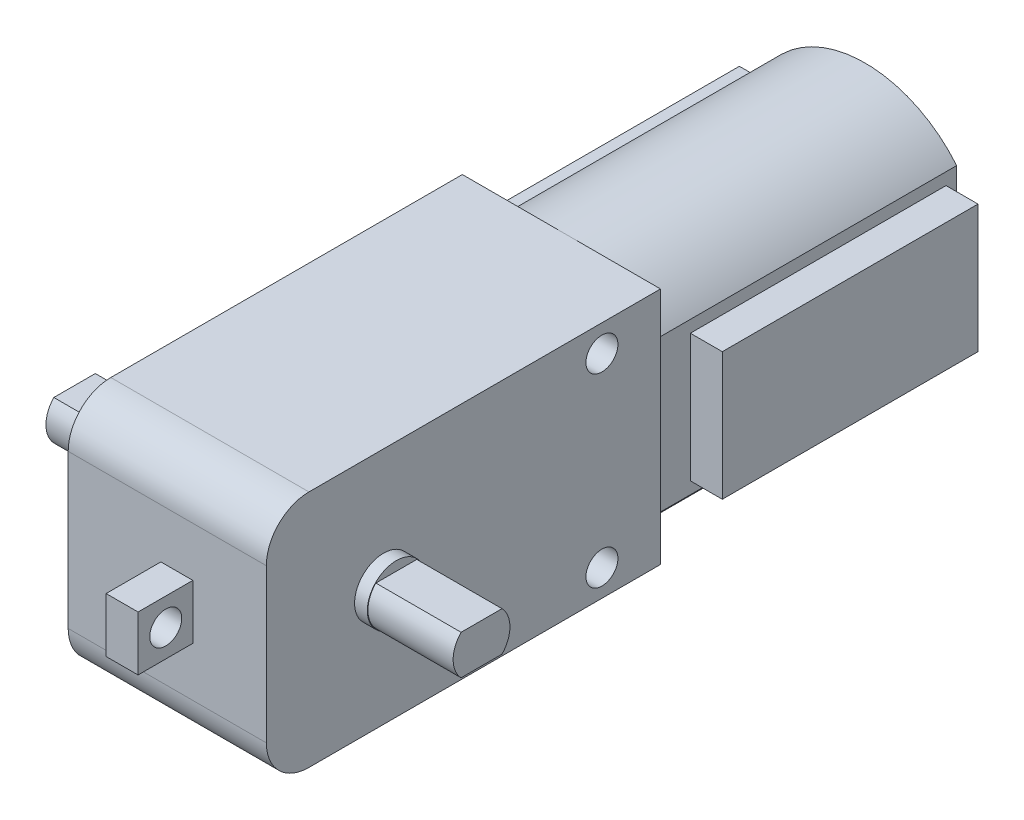
SolidWorks part; units mm, degrees
ref_plane "Front Plane" through (0, 0, 0) normal (0, 0, 1) x (1, 0, 0)
ref_plane "Top Plane" through (0, 0, 0) normal (0, 1, 0) x (1, 0, 0)
ref_plane "Right Plane" through (0, 0, 0) normal (1, 0, 0) x (0, 0, -1)
sketch "Sketch1" plane through (0, 0, 0) normal (1, 0, 0) x (0, 0, -1)
  line L1 (-18.5, 11.2) -> (18.5, 11.2)
  line L2 (-18.5, 11.2) -> (-18.5, -11.2)
  line L3 (-18.5, -11.2) -> (18.5, -11.2)
  line L4 (18.5, 11.2) -> (18.5, -11.2)
  dimension "D1" = 37
  dimension "D2" = 22.4
  dimension "D3" = 18.5
  dimension "D4" = 11.2
extrude "Boss-Extrude1" add sketch "Sketch1" along normal blind 18.6
fillet "Fillet1" radius 4 2 edges at (9.3, -11.2, 18.5) (9.3, 11.2, 18.5)
sketch "Sketch2" plane through (0, 0, 0) normal (-1, 0, 0) x (0, 0, 1)
  line L0 (18.5, 7.2) -> (18.5, -7.2) construction
  circle A0 centre (7.5, 0) radius 3.65
  point P3 (18.5, 0)
  dimension "D1" = 7.3
  dimension "D2" = 11
extrude "Boss-Extrude2" add sketch "Sketch2" along normal blind 1.2
sketch "Sketch3" plane through (-1.2, 0, 0) normal (-1, 0, 0) x (0, 0, 1)
  circle A0 centre (7.5, 0) radius 2.73
  dimension "D1" = 5.46
extrude "Boss-Extrude3" add sketch "Sketch3" along normal blind 1.2
sketch "Sketch4" plane through (-2.4, 0, 0) normal (-1, 0, 0) x (0, 0, 1)
  line L0 (5.5528, -1.85) -> (9.4472, -1.85)
  line L1 (5.5528, 1.85) -> (9.4472, 1.85)
  arc A0 (5.5528, 1.85) -> (5.5528, -1.85) centre (7.5, 0) ccw
  arc A1 (9.4472, -1.85) -> (9.4472, 1.85) centre (7.5, 0) ccw
  dimension "D1" = 3.7
  dimension "D2" = 1.85
extrude "Boss-Extrude4" add sketch "Sketch4" along normal blind 8
sketch "Sketch5" plane through (18.6, 0, 0) normal (1, 0, 0) x (0, 0, -1)
  line L0 (-18.5, 7.2) -> (-18.5, -7.2) construction
  circle A0 centre (-7.5, 0) radius 2.72
  point P2 (-18.5, 0)
  dimension "D1" = 5.44
  dimension "D2" = 11
extrude "Boss-Extrude5" add sketch "Sketch5" along normal blind 1.2
sketch "Sketch6" plane through (19.8, 0, 0) normal (1, 0, 0) x (0, 0, -1)
  line L0 (-9.4199, -1.85) -> (-5.5801, -1.85)
  line L1 (-9.4199, 1.85) -> (-5.5801, 1.85)
  arc A0 (-9.4199, 1.85) -> (-9.4199, -1.85) centre (-7.5, 0) ccw
  arc A1 (-5.5801, -1.85) -> (-5.5801, 1.85) centre (-7.5, 0) ccw
  dimension "D1" = 3.7
  dimension "D2" = 1.85
extrude "Boss-Extrude6" add sketch "Sketch6" along normal blind 8
sketch "Sketch7" plane through (0, 0, 0) normal (-1, 0, 0) x (0, 0, 1)
  line L0 (18.5, 7.2) -> (18.5, -7.2) construction
  circle A0 centre (-3.9, 0) radius 2
  dimension "D1" = 4
  dimension "D2" = 22.4
extrude "Boss-Extrude7" add sketch "Sketch7" along normal blind 2.4
ref_plane "Plane1" through (10.2, 0, 0) normal (-1, 0, 0) x (0, 0, 1)
sketch "Sketch8" plane through (10.2, 0, 0) normal (-1, 0, 0) x (0, 0, 1)
  line L0 (18.5, 7.2) -> (18.5, -7.2) construction
  line L1 (18.5, -2.56) -> (23.64, -2.56)
  line L2 (18.5, -2.56) -> (18.5, 2.56)
  line L3 (18.5, 2.56) -> (23.64, 2.56)
  line L4 (23.64, -2.56) -> (23.64, 2.56)
  dimension "D1" = 5.14
  dimension "D2" = 5.12
  dimension "D3" = 2.56
extrude "Boss-Extrude8" add sketch "Sketch8" along normal mid plane 3
sketch "Sketch11" plane through (0, 0, -18.5) normal (0, 0, -1) x (-1, 0, 0)
  line L0 (-18.6, -11.2) -> (-18.6, 11.2) construction
  line L1 (-18.4, 7.128) -> (-18.4, -7.128)
  line L2 (-1.2, 7.128) -> (-1.2, -7.128)
  arc A0 (-1.2, 7.128) -> (-18.4, 7.128) centre (-9.8, 0) ccw
  arc A1 (-18.4, -7.128) -> (-1.2, -7.128) centre (-9.8, 0) ccw
  dimension "D2" = 22.34
  dimension "D1" = 8.8
  dimension "D3" = 17.2
  dimension "D4" = 8.6
extrude "Boss-Extrude10" add sketch "Sketch11" along normal blind 28
sketch "Sketch12" plane through (18.4, 0, 0) normal (1, 0, 0) x (0, 0, -1)
  line L0 (18.5, -11.2) -> (18.5, 11.2) construction
  line L1 (21.5, 6) -> (45.5, 6)
  line L2 (21.5, 6) -> (21.5, -6)
  line L3 (21.5, -6) -> (45.5, -6)
  line L4 (45.5, 6) -> (45.5, -6)
  dimension "D1" = 3
  dimension "D2" = 6
  dimension "D3" = 24
  dimension "D4" = 12
extrude "Boss-Extrude11" add sketch "Sketch12" along normal blind 3
mirror "Mirror1" about plane through (10.2, 0, 0) normal (-1, 0, 0) of "Boss-Extrude11"
sketch "Sketch13" plane through (18.6, 0, 0) normal (1, 0, 0) x (0, 0, -1)
  line L0 (-14.5, -11.2) -> (18.5, -11.2) construction
  line L1 (-18.5, 7.2) -> (-18.5, -7.2) construction
  circle A0 centre (13, -8.7) radius 1.5
  dimension "D1" = 3
  dimension "D2" = 2.5
  dimension "D3" = 31.5
extrude "Cut-Extrude1" cut sketch "Sketch13" against normal blind 28
mirror "Mirror2" about plane through (0, 0, 0) normal (0, 1, 0) of "Cut-Extrude1"
sketch "Sketch14" plane through (8.7, 0, 0) normal (-1, 0, 0) x (0, 0, 1)
  line L0 (23.64, -2.56) -> (23.64, 2.56) construction
  circle A0 centre (21.04, 0) radius 1.5
  dimension "D1" = 3
  dimension "D2" = 2.6
extrude "Cut-Extrude2" cut sketch "Sketch14" against normal blind 28
